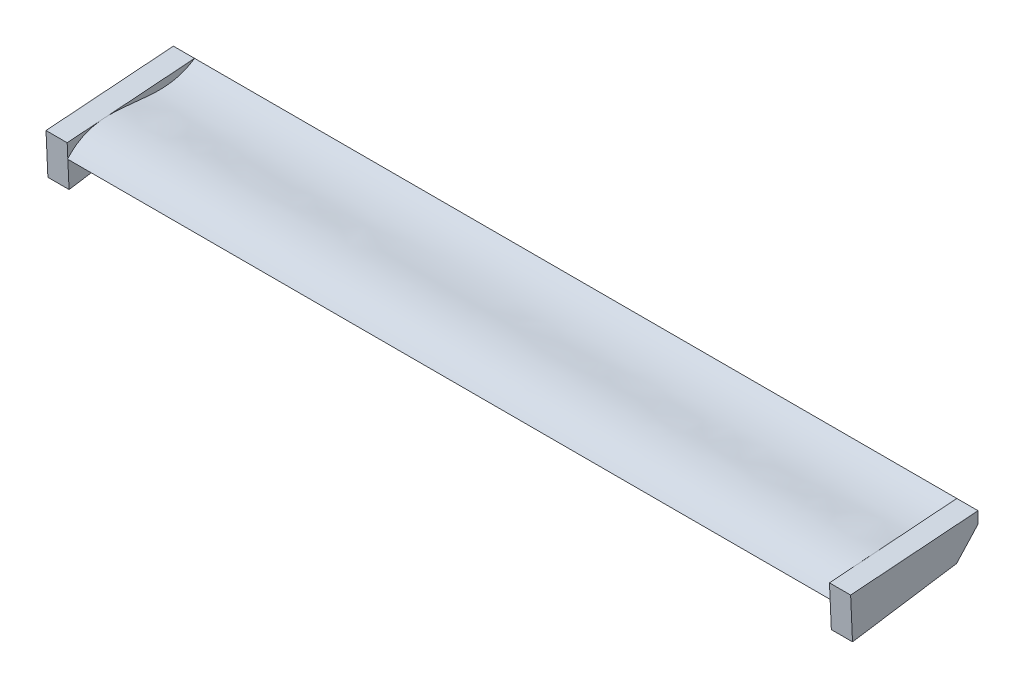
SolidWorks part; units mm, degrees
ref_plane "Front" through (0, 0, 0) normal (0, 0, 1) x (1, 0, 0)
ref_plane "Top" through (0, 0, 0) normal (0, 1, 0) x (1, 0, 0)
ref_plane "Right" through (0, 0, 0) normal (1, 0, 0) x (0, 0, -1)
sketch "Sketch5" plane through (0, 0, 0) normal (1, 0, 0) x (0, 0, -1)
  line L0 (41.91, 0) -> (-41.91, 0) construction
  spline S0 degree 3 poles (-28.3354, 0) (-4.2203, -13.4828) (29.9192, -7.4095) (47.8646, 14.23) knots 0 0 0 0 1 1 1 1
  spline S1 degree 3 poles (-28.3354, 0) (-7.388, 23.3297) (23.9521, -2.2197) (47.8646, 14.23) knots 0 0 0 0 1 1 1 1
  dimension "D1" = 76.2
extrude "Boss-Extrude2" add sketch "Sketch5" along normal mid plane 457.2
sketch "Sketch7" plane through (228.6, 0, 0) normal (1, 0, 0) x (0, 0, -1)
  line L0 (47.8646, 14.23) -> (-28.5305, 8.5936)
  line L1 (-28.5305, 8.5936) -> (-27.3991, -16.2983)
  line L2 (-27.3991, -16.2983) -> (35.0047, -6.8115)
  line L3 (35.0047, -6.8115) -> (47.8646, 7.201)
  line L4 (47.8646, 7.201) -> (47.8646, 14.23)
extrude "Boss-Extrude3" add sketch "Sketch7" along normal blind 12.7
sketch "Sketch8" plane through (-228.6, 0, 0) normal (-1, 0, 0) x (0, 0, 1)
  line L0 (28.5305, 8.5936) -> (27.3991, -16.2983)
  line L1 (27.3991, -16.2983) -> (-35.0047, -6.8115)
  line L2 (-35.0047, -6.8115) -> (-47.8646, 7.201)
  line L3 (-47.8646, 7.201) -> (-47.8646, 14.23)
  line L4 (-47.8646, 14.23) -> (28.5305, 8.5936)
extrude "Boss-Extrude4" add sketch "Sketch8" along normal blind 12.7
